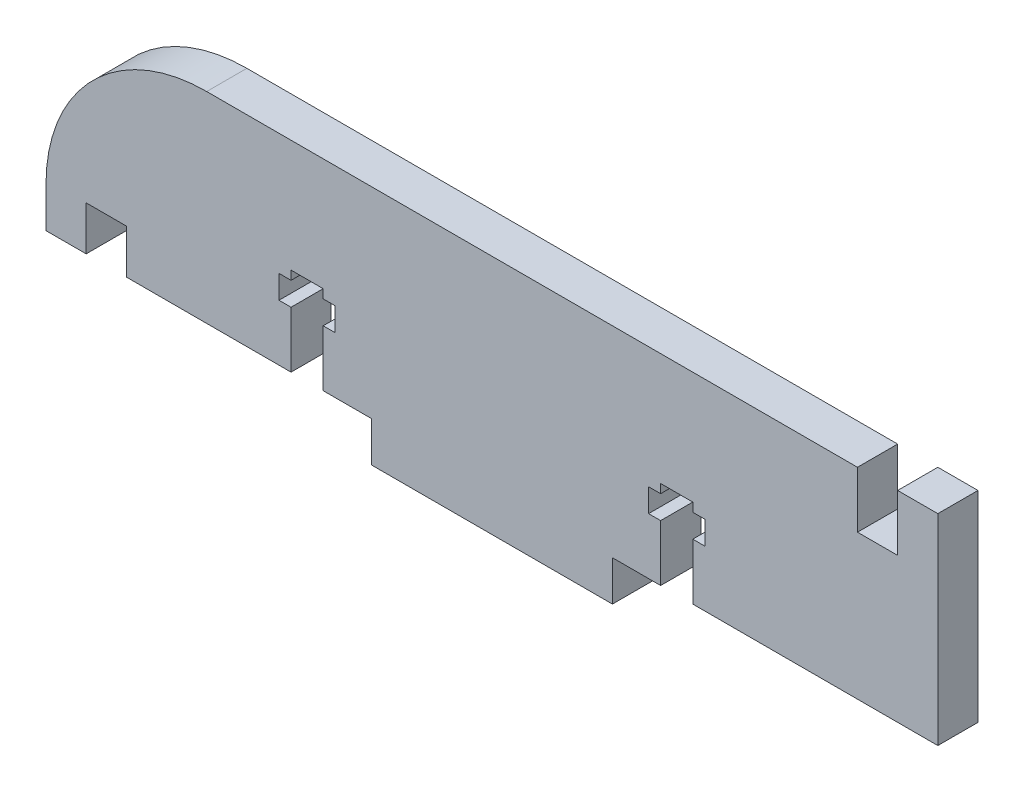
SolidWorks part; units mm, degrees
ref_plane "前视基准面" through (0, 0, 0) normal (0, 0, 1) x (1, 0, 0)
ref_plane "上视基准面" through (0, 0, 0) normal (0, 1, 0) x (1, 0, 0)
ref_plane "右视基准面" through (0, 0, 0) normal (1, 0, 0) x (0, 0, -1)
sketch "草图1" plane through (0, 0, 0) normal (0, 0, 1) x (1, 0, 0)
  line L0 (-80.5, 0) -> (-76.5, 0)
  line L1 (0, 0) -> (-111, 0)
  line L2 (0, 0) -> (0, 25)
  line L3 (0, 25) -> (-111, 25)
  line L4 (-111, 0) -> (-111, 25)
  line L5 (-70.5, 0) -> (-40.5, 0)
  line L6 (-70.5, 0) -> (-70.5, -5)
  line L7 (-70.5, -5) -> (-40.5, -5)
  line L8 (-40.5, 0) -> (-40.5, -5)
  line L9 (-80.5, 0) -> (-80.5, 11)
  line L10 (-80.5, 11) -> (-76.5, 11)
  line L11 (-76.5, 0) -> (-76.5, 11)
  line L12 (-82, 9.9) -> (-75, 9.9)
  line L13 (-82, 9.9) -> (-82, 7)
  line L14 (-82, 7) -> (-75, 7)
  line L15 (-75, 9.9) -> (-75, 7)
  line L16 (-55.5, 25) -> (-55.5, 0) construction
  line L17 (-36, 9.9) -> (-36, 7)
  line L18 (-34.5, 0) -> (-34.5, 11)
  line L19 (-29, 7) -> (-36, 7)
  line L20 (-29, 9.9) -> (-29, 7)
  line L21 (-30.5, 0) -> (-30.5, 11)
  line L22 (-29, 9.9) -> (-36, 9.9)
  line L23 (-30.5, 11) -> (-34.5, 11)
  line L25 (-106, 0) -> (-101, 0)
  line L26 (-106, 0) -> (-106, 5.5)
  line L27 (-106, 5.5) -> (-101, 5.5)
  line L28 (-101, 0) -> (-101, 5.5)
  line L29 (-10, 25) -> (-5, 25)
  line L30 (-10, 25) -> (-10, 18)
  line L31 (-10, 18) -> (-5, 18)
  line L32 (-5, 25) -> (-5, 18)
  point P17 (-82, 8.45)
  point P18 (-70.5, -2.5)
  dimension "D1" = 111
  dimension "D2" = 5
  dimension "D3" = 30
  dimension "D4" = 4
  dimension "D5" = 7
  dimension "D6" = 2.9
  dimension "D7" = 1.5
  dimension "D8" = 0
  dimension "D9" = 11
  dimension "D10" = 7
  dimension "D11" = 6
  dimension "D12" = 15
  dimension "D13" = 25
  dimension "D14" = 5
  dimension "D15" = 5
  dimension "D16" = 5.5
  dimension "D17" = 18
  dimension "D18" = 5
  dimension "D19" = 5
  dimension "D20" = 91
extrude "凸台-拉伸1" add sketch "草图1" along normal blind 5 contours L16 L3 L4 L1 L26 L27 L28 L9 L14 L13 L12 L10 L11 L15 L5 | L3 L16 L1 L18 L19 L17 L22 L23 L21 L20 L2 L32 L31 L30
fillet "圆角1" radius 20 1 edges at (-111, 25, 2.5)
